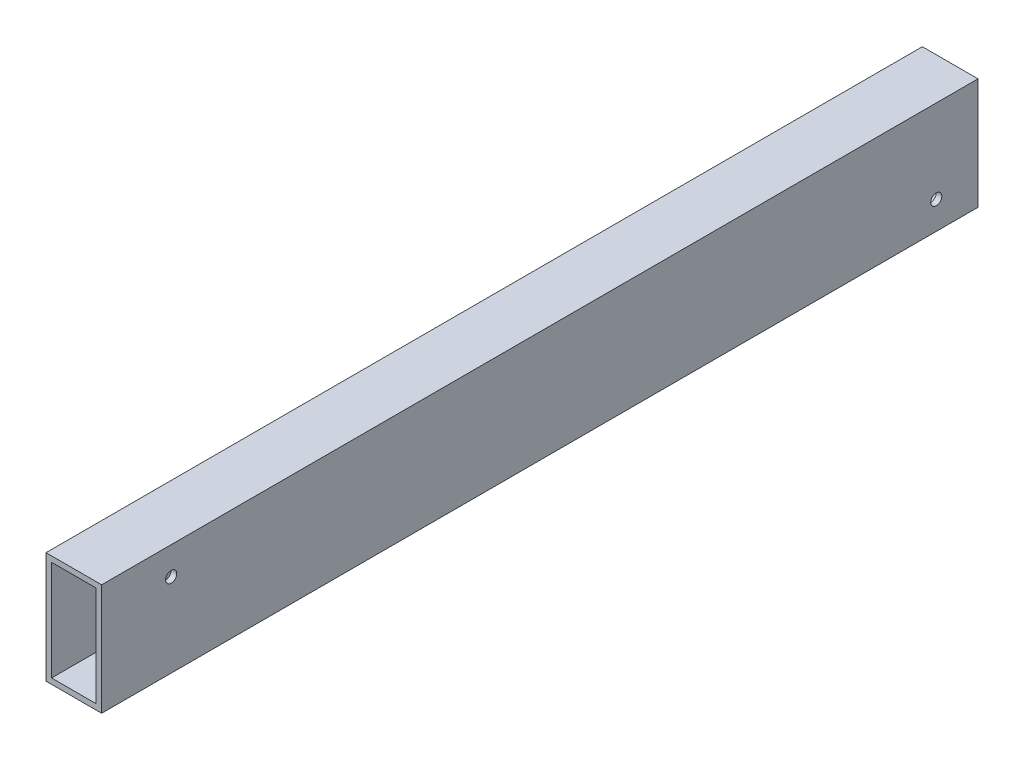
SolidWorks part; units mm, degrees
material "1060 合金"
ref_plane "前视基准面" through (0, 0, 0) normal (0, 0, 1) x (1, 0, 0)
ref_plane "上视基准面" through (0, 0, 0) normal (0, 1, 0) x (1, 0, 0)
ref_plane "右视基准面" through (0, 0, 0) normal (1, 0, 0) x (0, 0, -1)
other "Configuration Table"
sketch "草图1" plane through (0, 0, 0) normal (0, 0, 1) x (1, 0, 0)
  line L1 (0, 0) -> (20, 0)
  line L2 (0, 0) -> (0, 40)
  line L3 (0, 40) -> (20, 40)
  line L4 (20, 0) -> (20, 40)
  line L5 (2, 2) -> (18, 2)
  line L6 (2, 2) -> (2, 38)
  line L7 (2, 38) -> (18, 38)
  line L8 (18, 2) -> (18, 38)
  dimension "D1" = 20
  dimension "D2" = 40
  dimension "D3" = 2
  dimension "D4" = 2
  dimension "D5" = 2
  dimension "D6" = 2
extrude "凸台-拉伸1" add sketch "草图1" along normal blind 315
sketch "草图2" plane through (20, 0, 0) normal (1, 0, 0) x (0, 0, -1)
  line L0 (-328.752, 30) -> (-7.0045, 30) construction
  line L1 (0, 0) -> (0, 40) construction
  line L2 (-315, 40) -> (0, 40) construction
  line L4 (-315, 0) -> (-315, 40) construction
  line L6 (-315, 0) -> (0, 0) construction
  circle A0 centre (-290, 30) radius 2
  circle A2 centre (-15, 10) radius 2
  dimension "D1" = 4
  dimension "D2" = 4
  dimension "D3" = 15
  dimension "D4" = 25
  dimension "D5" = 30
  dimension "D6" = 30
extrude "切除-拉伸1" cut sketch "草图2" against normal through all
sketch "草图3" plane through (0, 0, 0) normal (-1, 0, 0) x (0, 0, 1)
  circle A0 centre (10, 17.65) radius 1.75
  circle A1 centre (30, 17.65) radius 1.75
  circle A2 centre (50, 17.65) radius 1.75
  circle A3 centre (70, 17.65) radius 1.75
  circle A4 centre (90, 17.65) radius 1.75
  circle A5 centre (110, 17.65) radius 1.75
  circle A6 centre (130, 17.65) radius 1.75
  circle A7 centre (150, 17.65) radius 1.75
  circle A8 centre (170, 17.65) radius 1.75
  circle A9 centre (190, 17.65) radius 1.75
  circle A10 centre (210, 17.65) radius 1.75
  circle A11 centre (230, 17.65) radius 1.75
  circle A12 centre (250, 17.65) radius 1.75
  circle A13 centre (270, 17.65) radius 1.75
  circle A14 centre (190, 17.65) radius 3 construction
  dimension "D1" = 3.5
  dimension "D2" = 3.5
  dimension "D3" = 3.5
  dimension "D4" = 3.5
  dimension "D5" = 1.25
  dimension "D6" = 3.5
  dimension "D7" = 3.5
  dimension "D8" = 3.5
  dimension "D9" = 3.5
  dimension "D10" = 3.5
  dimension "D11" = 3.5
  dimension "D12" = 3.5
  dimension "D13" = 3.5
  dimension "D14" = 3.5
extrude "切除-拉伸2" cut sketch "草图3" against normal blind 2
sketch "草图4" plane through (0, 0, 0) normal (0, -1, 0) x (-1, 0, 0)
  circle A0 centre (-10, -10) radius 1.75
  circle A1 centre (-10, -30) radius 1.75
  circle A2 centre (-10, -50) radius 1.75
  circle A3 centre (-10, -70) radius 1.75
  circle A4 centre (-10, -90) radius 1.75
  circle A5 centre (-10, -110) radius 1.75
  circle A6 centre (-10, -130) radius 1.75
  circle A7 centre (-10, -150) radius 1.75
  circle A8 centre (-10, -170) radius 1.75
  circle A9 centre (-10, -190) radius 1.75
  circle A10 centre (-10, -210) radius 1.75
  circle A11 centre (-10, -230) radius 1.75
  circle A12 centre (-10, -250) radius 1.75
  circle A13 centre (-10, -270) radius 1.75
  circle A14 centre (-10, -50) radius 3 construction
  dimension "D1" = 3.5
  dimension "D2" = 3.5
  dimension "D3" = 3.5
  dimension "D4" = 3.5
  dimension "D5" = 3.5
  dimension "D6" = 3.5
  dimension "D7" = 3.5
  dimension "D8" = 3.5
  dimension "D9" = 3.5
  dimension "D10" = 3.5
  dimension "D11" = 3.5
  dimension "D12" = 1.25
  dimension "D13" = 3.5
  dimension "D14" = 3.5
extrude "切除-拉伸3" cut sketch "草图4" against normal blind 2
